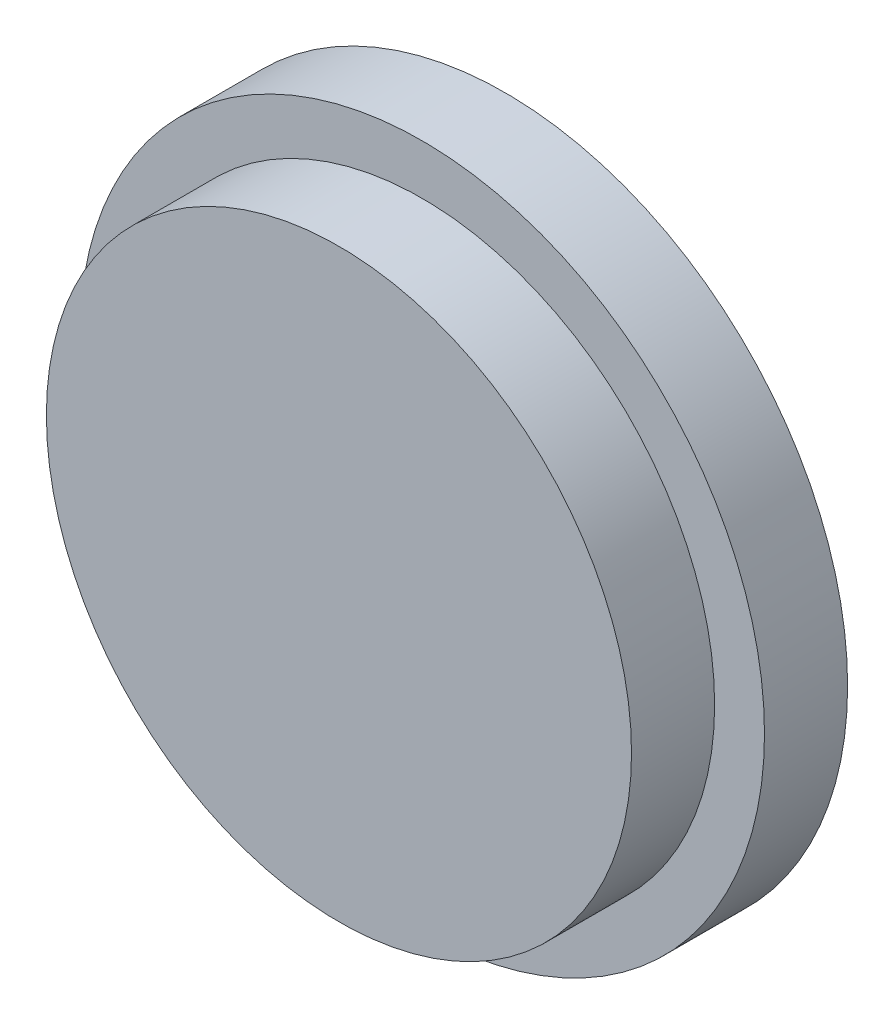
SolidWorks part; units mm, degrees
ref_plane "前视基准面" through (0, 0, 0) normal (0, 0, 1) x (1, 0, 0)
ref_plane "上视基准面" through (0, 0, 0) normal (0, 1, 0) x (1, 0, 0)
ref_plane "右视基准面" through (0, 0, 0) normal (1, 0, 0) x (0, 0, -1)
sketch "草图1" plane through (0, 0, 0) normal (0, 0, 1) x (1, 0, 0)
  circle A0 centre (0, 0) radius 41.2
extrude "凸台-拉伸1" add sketch "草图1" along normal blind 20
sketch "草图2" plane through (0, 0, 20) normal (0, 0, 1) x (1, 0, 0)
  circle A0 centre (0, 0) radius 35.2
extrude "切除-拉伸1" cut sketch "草图2" against normal blind 10 flip side to cut
sketch "草图3" plane through (0, 0, 20) normal (0, 0, 1) x (1, 0, 0)
  line L0 (0, 41.2) -> (0, -41.2)
  circle A0 centre (0, 0) radius 41.2 construction
